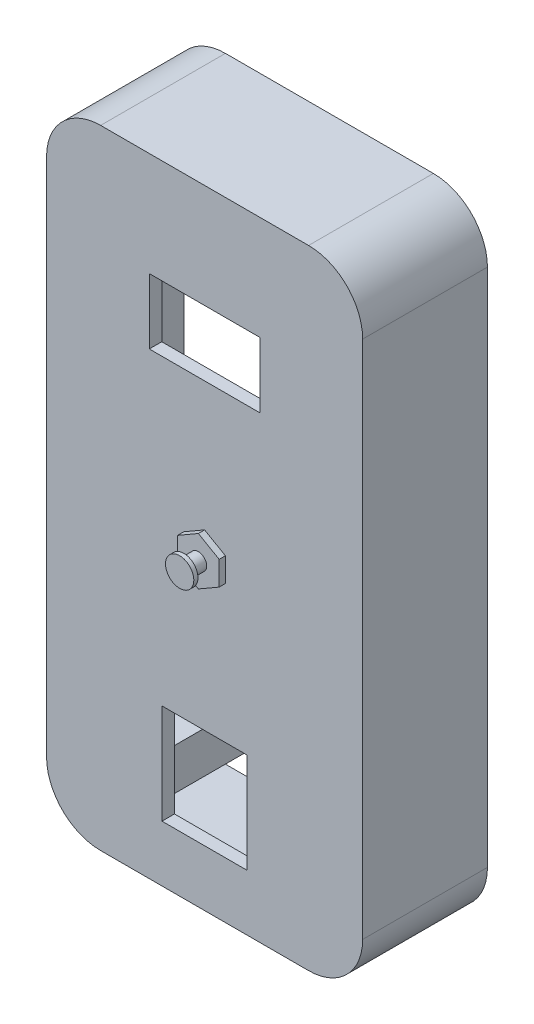
SolidWorks part; units mm, degrees
ref_plane "Front Plane" through (0, 0, 0) normal (0, 0, 1) x (1, 0, 0)
ref_plane "Top Plane" through (0, 0, 0) normal (0, 1, 0) x (1, 0, 0)
ref_plane "Right Plane" through (0, 0, 0) normal (1, 0, 0) x (0, 0, -1)
sketch "Sketch1" plane through (0, 0, 0) normal (0, 0, 1) x (1, 0, 0)
  line L0 (-25, 75.5) -> (25, 75.5)
  line L1 (-25, 72.5) -> (25, 72.5)
  line L2 (-35, 62.5) -> (-35, -62.5)
  line L3 (-25, -72.5) -> (25, -72.5)
  line L4 (35, 62.5) -> (35, -62.5)
  line L5 (-35, 72.5) -> (35, -72.5) construction
  line L6 (-35, -72.5) -> (35, 72.5) construction
  line L7 (38, 62.5) -> (38, -62.5)
  line L8 (-25, -75.5) -> (25, -75.5)
  line L9 (-38, 62.5) -> (-38, -62.5)
  arc A0 (-35, -62.5) -> (-25, -72.5) centre (-25, -62.5) ccw
  arc A1 (25, -72.5) -> (35, -62.5) centre (25, -62.5) ccw
  arc A2 (25, 72.5) -> (35, 62.5) centre (25, 62.5) cw
  arc A3 (-25, 72.5) -> (-35, 62.5) centre (-25, 62.5) ccw
  arc A4 (25, 75.5) -> (38, 62.5) centre (25, 62.5) cw
  arc A5 (25, -75.5) -> (38, -62.5) centre (25, -62.5) ccw
  arc A6 (-38, -62.5) -> (-25, -75.5) centre (-25, -62.5) ccw
  arc A7 (-25, 75.5) -> (-38, 62.5) centre (-25, 62.5) ccw
  point P0 (0, 0)
  dimension "D3" = 10
  dimension "D1" = 70
  dimension "D2" = 145
  dimension "D4" = 3
extrude "Boss-Extrude1" add sketch "Sketch1" against normal blind 30
sketch "Sketch6" plane through (0, 0, 0) normal (0, 0, 1) x (1, 0, 0)
  line L0 (38, -62.5) -> (38, 62.5) construction
  line L1 (-23, -75.5) -> (23, -75.5)
  line L2 (-38, -60.5) -> (-38, 60.5)
  line L3 (-23, 75.5) -> (23, 75.5)
  line L4 (38, -60.5) -> (38, 60.5)
  line L5 (-38, -75.5) -> (38, 75.5) construction
  line L6 (-38, 75.5) -> (38, -75.5) construction
  line L7 (25, 75.5) -> (-25, 75.5) construction
  arc A0 (-23, -75.5) -> (-38, -60.5) centre (-23, -60.5) cw
  arc A1 (23, -75.5) -> (38, -60.5) centre (23, -60.5) ccw
  arc A2 (23, 75.5) -> (38, 60.5) centre (23, 60.5) cw
  arc A3 (-38, 60.5) -> (-23, 75.5) centre (-23, 60.5) cw
  point P0 (0, 0)
  dimension "D3" = 15
extrude "Boss-Extrude2" add sketch "Sketch6" against normal blind 3
sketch "Sketch7" plane through (0, 0, 0) normal (0, 0, 1) x (1, 0, 0)
  line L0 (-39.6446, -2) -> (-28.4, -2) construction
  line L1 (-13.3, 50.5) -> (13.3, 50.5)
  line L2 (-13.3, 50.5) -> (-13.3, 34.8)
  line L3 (-13.3, 34.8) -> (13.3, 34.8)
  line L4 (13.3, 50.5) -> (13.3, 34.8)
  line L5 (-13.3, 50.5) -> (13.3, 34.8) construction
  line L6 (-13.3, 34.8) -> (13.3, 50.5) construction
  line L7 (25, 75.5) -> (-25, 75.5) construction
  line L8 (0, 0) -> (0, -50) construction
  line L9 (-21.6, -2) -> (21.6, -2) construction
  line L10 (-10.25, -38) -> (10.25, -38)
  line L11 (-10.25, -38) -> (-10.25, -62)
  line L12 (-10.25, -62) -> (10.25, -62)
  line L13 (10.25, -38) -> (10.25, -62)
  line L14 (-10.25, -38) -> (10.25, -62) construction
  line L15 (-10.25, -62) -> (10.25, -38) construction
  line L16 (28.4, -2) -> (39.2631, -2) construction
  circle A1 centre (0, -2) radius 3.4
  point P0 (0, 42.65)
  dimension "D5" = 6.8
  dimension "D1" = 26.6
  dimension "D2" = 15.7
  dimension "D4" = 25
  dimension "D8" = 50
  dimension "D9" = 24
  dimension "D10" = 20.5
extrude "Cut-Extrude1" cut sketch "Sketch7" against normal blind 3
sketch "Sketch8" plane through (0, 0, -3) normal (0, 0, -1) x (-1, 0, 0)
  line L0 (0, 0) -> (0, 46.8611) construction
  line L1 (0, 0) -> (26.3683, 0) construction
  line L2 (-25, 72.5) -> (25, 72.5) construction
  line L3 (-30, 67.5) -> (-20, 67.5)
  line L4 (-30, 67.5) -> (-30, 57.5)
  line L5 (-30, 57.5) -> (-20, 57.5)
  line L6 (-20, 67.5) -> (-20, 57.5)
  line L7 (-30, 67.5) -> (-20, 57.5) construction
  line L8 (-30, 57.5) -> (-20, 67.5) construction
  line L9 (-35, -62.5) -> (-35, 62.5) construction
  line L10 (30, 57.5) -> (20, 67.5) construction
  line L11 (30, 67.5) -> (20, 57.5) construction
  line L12 (20, 67.5) -> (20, 57.5)
  line L13 (30, 57.5) -> (20, 57.5)
  line L14 (30, 67.5) -> (30, 57.5)
  line L15 (30, 67.5) -> (20, 67.5)
  line L16 (30, -67.5) -> (20, -57.5) construction
  line L17 (30, -57.5) -> (20, -67.5) construction
  line L18 (30, -67.5) -> (20, -67.5)
  line L19 (30, -67.5) -> (30, -57.5)
  line L20 (30, -57.5) -> (20, -57.5)
  line L21 (20, -67.5) -> (20, -57.5)
  line L22 (-30, -57.5) -> (-20, -67.5) construction
  line L23 (-30, -67.5) -> (-20, -57.5) construction
  line L24 (-20, -67.5) -> (-20, -57.5)
  line L25 (-30, -57.5) -> (-20, -57.5)
  line L26 (-30, -67.5) -> (-30, -57.5)
  line L27 (-30, -67.5) -> (-20, -67.5)
  point P3 (-25, 62.5)
  point P17 (25, 62.5)
  point P22 (25, -62.5)
  point P27 (-25, -62.5)
  dimension "D1" = 10
  dimension "D2" = 10
  dimension "D3" = 5
  dimension "D4" = 5
extrude "Boss-Extrude3" add sketch "Sketch8" along normal blind 27
sketch "Sketch9" plane through (0, 0, -30) normal (0, 0, -1) x (-1, 0, 0)
  line L0 (-35, 0) -> (35, 0) construction
  line L1 (-35, -62.5) -> (-35, 62.5) construction
  line L2 (-28.4414, 89) -> (-28.4582, 90.0122) construction
  line L8 (28.4414, 89) -> (28.4582, 90.0122) construction
  line L16 (-24.9834, -65.5) -> (-25.0166, -65.5)
  line L17 (-20, 57.5) -> (-20, 67.5) construction
  line L18 (-20, 67.5) -> (-30, 67.5) construction
  line L19 (35, 62.5) -> (35, -62.5) construction
  line L20 (0, 75.5) -> (0, -75.5) construction
  line L21 (-25, 75.5) -> (25, 75.5) construction
  line L22 (25, -75.5) -> (-25, -75.5) construction
  arc A4 (-25.0166, -65.5) -> (-24.9834, -65.5) centre (-25, -62.5) ccw
  circle A8 centre (-25, 62.5) radius 3
  circle A9 centre (25, 62.5) radius 3
  circle A10 centre (25, -62.5) radius 3
  circle A11 centre (-25, -62.5) radius 3
  point P3 (0, 0)
  point P9 (0, 0)
  point P11 (0, 0)
  point P13 (0, 0)
  point P18 (0, 0)
  point P20 (-20, 62.5)
  point P25 (0, 0)
  point P28 (28, -62.5)
  point P35 (-25, 67.5)
  dimension "D2" = 6
extrude "Cut-Extrude2" cut sketch "Sketch9" against normal blind 20 contours A8 | A9 | A11 L16 | A10
sketch "Sketch10" plane through (-38, 0, 0) normal (-1, 0, 0) x (0, 0, 1)
  line L0 (0, 62.5) -> (0, -62.5) construction
  line L1 (-22.5, 44.1368) -> (-10, 44.1368)
  line L2 (-22.5, 44.1368) -> (-22.5, 25.6368)
  line L3 (-22.5, 25.6368) -> (-10, 25.6368)
  line L4 (-10, 44.1368) -> (-10, 25.6368)
  dimension "D1" = 18.5
  dimension "D2" = 12.5
  dimension "D3" = 10
extrude "Cut-Extrude3" cut sketch "Sketch10" against normal blind 10
sketch "Sketch12" plane through (0, 0, 0) normal (0, 0, 1) x (1, 0, 0)
  line L1 (5, -4.8868) -> (5, 0.8868)
  line L2 (5, 0.8868) -> (0, 3.7735)
  line L3 (0, 3.7735) -> (-5, 0.8868)
  line L4 (-5, 0.8868) -> (-5, -4.8868)
  line L5 (-5, -4.8868) -> (0, -7.7735)
  line L6 (0, -7.7735) -> (5, -4.8868)
  circle A0 centre (0, -2) radius 5 construction
  point P1 (-5, -2)
  dimension "D1" = 10
extrude "Boss-Extrude4" add sketch "Sketch12" along normal blind 1.5
sketch "Sketch14" plane through (0, 0, 0) normal (0, 0, 1) x (1, 0, 0)
  circle A0 centre (0, -2) radius 2
  dimension "D1" = 4
extrude "Boss-Extrude5" add sketch "Sketch14" along normal blind 5
sketch "Sketch15" plane through (0, 0, 5) normal (0, 0, 1) x (1, 0, 0)
  circle A0 centre (0, -2) radius 3.4 construction
  circle A3 centre (0, -2) radius 3.4
extrude "Boss-Extrude6" add sketch "Sketch15" along normal blind 1
equation "\"length\"= 145"
equation "\"width\"= 70"
equation "\"D2@Sketch1\"=\"length\""
equation "\"D1@Sketch1\"=\"width\""
